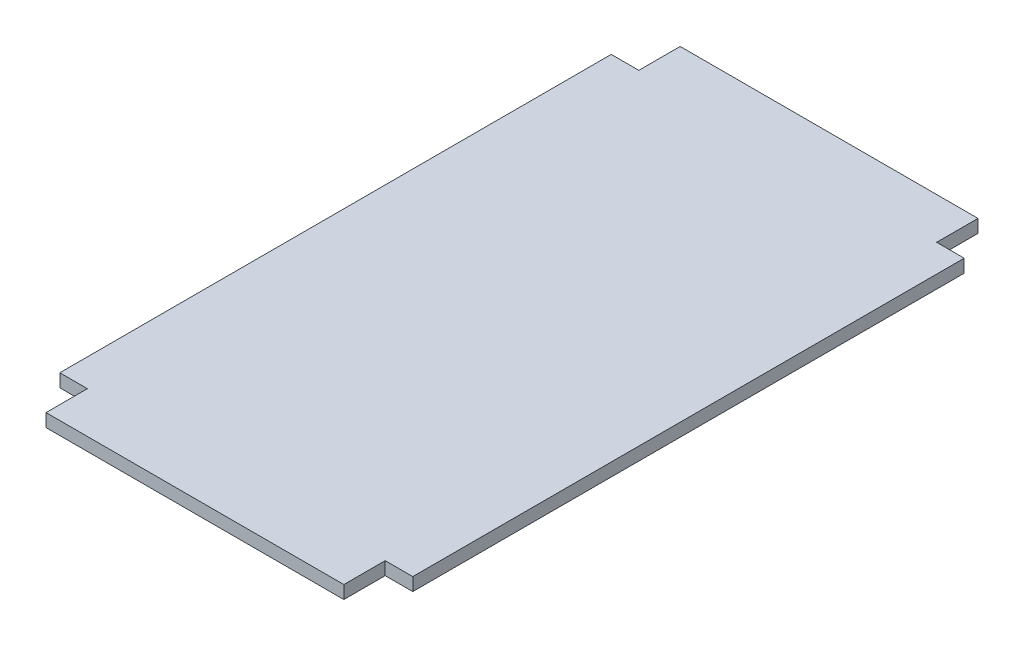
SolidWorks part; units mm, degrees
ref_plane "Front Plane" through (0, 0, 0) normal (0, 0, 1) x (1, 0, 0)
ref_plane "Top Plane" through (0, 0, 0) normal (0, 1, 0) x (1, 0, 0)
ref_plane "Right Plane" through (0, 0, 0) normal (1, 0, 0) x (0, 0, -1)
sketch "Sketch1" plane through (0, 0, 0) normal (0, 1, 0) x (1, 0, 0)
  line L0 (-40.6471, 66.4972) -> (40.6471, 66.4972) construction
  line L1 (40.6471, -73.025) -> (-40.6471, -73.025)
  line L2 (40.6471, -73.025) -> (40.6471, 73.025)
  line L3 (40.6471, 73.025) -> (-40.6471, 73.025)
  line L4 (-40.6471, -73.025) -> (-40.6471, 73.025)
  line L5 (40.6471, -73.025) -> (-40.6471, 73.025) construction
  line L6 (40.6471, 73.025) -> (-40.6471, -73.025) construction
  line L7 (-40.6471, -66.4972) -> (40.6471, -66.4972) construction
  line L8 (-40.6471, 66.4972) -> (-40.6471, -66.4972) construction
  line L9 (40.6471, 66.4972) -> (40.6471, -66.4972) construction
  line L20 (-40.6471, -73.025) -> (-34.2971, -73.025)
  line L29 (-40.6471, -73.025) -> (-40.6471, -63.5)
  line L34 (-40.6471, -63.5) -> (-34.2971, -63.5)
  line L35 (-34.2971, -73.025) -> (-34.2971, -63.5)
  line L36 (40.6471, -73.025) -> (34.2971, -73.025)
  line L37 (40.6471, -73.025) -> (40.6471, -63.5)
  line L38 (40.6471, -63.5) -> (34.2971, -63.5)
  line L39 (34.2971, -73.025) -> (34.2971, -63.5)
  line L40 (-40.6471, 73.025) -> (-34.2971, 73.025)
  line L41 (-40.6471, 73.025) -> (-40.6471, 63.5)
  line L42 (-40.6471, 63.5) -> (-34.2971, 63.5)
  line L43 (-34.2971, 73.025) -> (-34.2971, 63.5)
  line L44 (40.6471, 73.025) -> (34.2971, 73.025)
  line L45 (40.6471, 73.025) -> (40.6471, 63.5)
  line L46 (40.6471, 63.5) -> (34.2971, 63.5)
  line L47 (34.2971, 73.025) -> (34.2971, 63.5)
  point P0 (0, 0)
  point P10 (40.6471, 0)
  point P11 (40.6471, 0)
  point P24 (19.2491, -58.7209)
  dimension "D1" = 81.2943
  dimension "D2" = 146.05
  dimension "D3" = 132.9944
  dimension "D4" = 6.35
  dimension "D5" = 127
extrude "Boss-Extrude1" add sketch "Sketch1" along normal blind 2.9972
